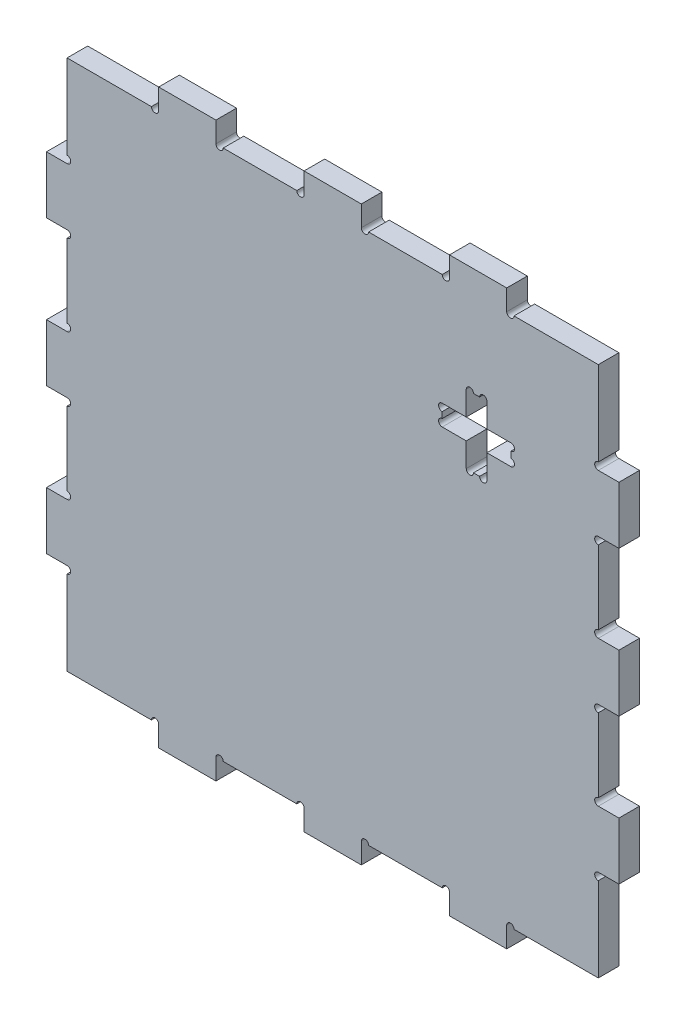
SolidWorks part; units mm, degrees
ref_plane "Piano frontale" through (0, 0, 0) normal (0, 0, 1) x (1, 0, 0)
ref_plane "Piano superiore" through (0, 0, 0) normal (0, 1, 0) x (1, 0, 0)
ref_plane "Piano destro" through (0, 0, 0) normal (1, 0, 0) x (0, 0, -1)
sketch "Schizzo1" plane through (0, 0, 0) normal (0, 0, 1) x (1, 0, 0)
  line L0 (-152, 250) -> (-152, 232)
  line L1 (-152, 250) -> (-102, 250)
  line L2 (232, 95.65) -> (232, 31.35)
  line L3 (232, 232) -> (232, 158.35)
  line L4 (250, 152) -> (250, 102)
  line L5 (-158.35, 232) -> (-232, 232)
  line L6 (-102, 250) -> (-102, 232)
  line L7 (-95.65, 232) -> (-31.35, 232)
  line L8 (-25, 232) -> (-25, 250)
  line L9 (-25, 250) -> (25, 250)
  line L10 (25, 250) -> (25, 232)
  line L11 (31.35, 232) -> (95.65, 232)
  line L12 (102, 232) -> (102, 250)
  line L13 (102, 250) -> (152, 250)
  line L14 (152, 250) -> (152, 232)
  line L15 (158.35, 232) -> (232, 232)
  line L16 (0, 0) -> (-543.7946, 0) construction
  line L17 (-25, 250) -> (25, 250)
  line L18 (102, 250) -> (152, 250)
  line L19 (0, 0) -> (250, 0) construction
  line L20 (127, -250) -> (127, -226.3396) construction
  line L21 (102, -250) -> (152, -250)
  line L22 (-25, -250) -> (25, -250)
  line L23 (152, -250) -> (152, -232)
  line L24 (102, -250) -> (152, -250)
  line L25 (102, -232) -> (102, -250)
  line L26 (31.35, -232) -> (95.65, -232)
  line L27 (25, -250) -> (25, -232)
  line L28 (-25, -250) -> (25, -250)
  line L29 (-25, -232) -> (-25, -250)
  line L30 (-95.65, -232) -> (-31.35, -232)
  line L31 (-102, -250) -> (-102, -232)
  line L32 (-152, -250) -> (-102, -250)
  line L33 (-152, -250) -> (-152, -232)
  line L34 (-158.35, 232) -> (-232, 232)
  line L35 (158.35, -232) -> (232, -232)
  line L36 (-232, -232) -> (-158.35, -232)
  line L37 (232, 152) -> (250, 152)
  line L38 (250, 152) -> (250, 102)
  line L39 (250, 102) -> (232, 102)
  line L40 (-232, -158.35) -> (-232, -232)
  line L41 (232, 25) -> (250, 25)
  line L42 (250, 25) -> (250, -25)
  line L43 (250, -25) -> (232, -25)
  line L44 (232, -31.35) -> (232, -95.65)
  line L45 (232, -102) -> (250, -102)
  line L46 (250, -102) -> (250, -152)
  line L47 (250, -152) -> (232, -152)
  line L48 (232, -158.35) -> (232, -232)
  line L49 (0, 0) -> (0, 361.2155) construction
  line L50 (-232, 232) -> (-232, 158.35)
  line L51 (-250, -152) -> (-232, -152)
  line L52 (-250, -102) -> (-250, -152)
  line L53 (250, 0) -> (195.0164, 0) construction
  line L54 (-232, -102) -> (-250, -102)
  line L55 (-232, -31.35) -> (-232, -95.65)
  line L56 (-250, -25) -> (-232, -25)
  line L57 (-250, 25) -> (-250, -25)
  line L58 (-232, 25) -> (-250, 25)
  line L59 (-250, 102) -> (-232, 102)
  line L60 (-250, 152) -> (-250, 102)
  line L61 (-232, 152) -> (-250, 152)
  line L62 (-250, 152) -> (-250, 102)
  line L63 (-232, 95.65) -> (-232, 31.35)
  line L64 (85.0518, 125.6467) -> (174.9168, 125.6467) construction
  line L65 (174.9168, 125.6467) -> (125.65, 90.1186) construction
  line L66 (125.65, 125.6467) -> (125.65, 176.559) construction
  line L67 (134.65, 95.6467) -> (133.3158, 95.6467)
  line L68 (134.65, 95.6467) -> (134.65, 116.6467)
  line L69 (95.65, 134.6467) -> (116.65, 134.6467)
  line L70 (95.65, 128.2967) -> (95.65, 122.9967)
  line L71 (95.65, 116.6467) -> (116.65, 116.6467)
  line L72 (155.65, 128.2967) -> (155.65, 122.9967)
  line L73 (128.3, 155.6467) -> (123, 155.6467)
  line L74 (116.65, 95.6467) -> (116.65, 116.6467)
  line L75 (128.3, 95.6467) -> (123, 95.6467)
  line L77 (134.65, 134.6467) -> (155.65, 134.6467)
  line L78 (134.65, 134.6467) -> (134.65, 155.6467)
  line L79 (134.65, 116.6467) -> (155.65, 116.6467)
  line L81 (116.65, 134.6467) -> (116.65, 155.6467)
  arc A0 (-152, 232) -> (-158.35, 232) centre (-155.175, 232) cw
  arc A1 (102, 232) -> (95.65, 232) centre (98.825, 232) cw
  arc A2 (-102, 232) -> (-95.65, 232) centre (-98.825, 232) ccw
  arc A3 (-25, 232) -> (-31.35, 232) centre (-28.175, 232) cw
  arc A4 (25, 232) -> (31.35, 232) centre (28.175, 232) ccw
  arc A5 (152, 232) -> (158.35, 232) centre (155.175, 232) ccw
  arc A6 (152, -232) -> (158.35, -232) centre (155.175, -232) cw
  arc A7 (25, -232) -> (31.35, -232) centre (28.175, -232) cw
  arc A8 (-25, -232) -> (-31.35, -232) centre (-28.175, -232) ccw
  arc A9 (-102, -232) -> (-95.65, -232) centre (-98.825, -232) cw
  arc A10 (102, -232) -> (95.65, -232) centre (98.825, -232) ccw
  arc A11 (-152, -232) -> (-158.35, -232) centre (-155.175, -232) ccw
  arc A12 (232, 102) -> (232, 95.65) centre (232, 98.825) ccw
  arc A13 (232, 152) -> (232, 158.35) centre (232, 155.175) cw
  arc A14 (232, -25) -> (232, -31.35) centre (232, -28.175) ccw
  arc A15 (232, 25) -> (232, 31.35) centre (232, 28.175) cw
  arc A16 (232, -102) -> (232, -95.65) centre (232, -98.825) cw
  arc A17 (232, -152) -> (232, -158.35) centre (232, -155.175) ccw
  arc A18 (-232, -152) -> (-232, -158.35) centre (-232, -155.175) cw
  arc A19 (-232, -102) -> (-232, -95.65) centre (-232, -98.825) ccw
  arc A20 (-232, 25) -> (-232, 31.35) centre (-232, 28.175) ccw
  arc A21 (-232, -25) -> (-232, -31.35) centre (-232, -28.175) cw
  arc A22 (-232, 152) -> (-232, 158.35) centre (-232, 155.175) ccw
  arc A23 (-232, 102) -> (-232, 95.65) centre (-232, 98.825) cw
  arc A24 (134.65, 155.6467) -> (128.3, 155.6467) centre (131.475, 155.6467) ccw
  arc A25 (116.65, 155.6467) -> (123, 155.6467) centre (119.825, 155.6467) cw
  arc A26 (134.65, 95.6467) -> (128.3, 95.6467) centre (131.475, 95.6467) cw
  arc A27 (116.65, 95.6467) -> (123, 95.6467) centre (119.825, 95.6467) ccw
  arc A28 (95.65, 116.6467) -> (95.65, 122.9967) centre (95.65, 119.8217) cw
  arc A29 (95.65, 134.6467) -> (95.65, 128.2967) centre (95.65, 131.4717) ccw
  arc A30 (155.65, 116.6467) -> (155.65, 122.9967) centre (155.65, 119.8217) ccw
  arc A31 (155.65, 134.6467) -> (155.65, 128.2967) centre (155.65, 131.4717) cw
  point P31 (250, 0)
  point P33 (-250, 0)
  point P113 (125.65, 125.6467)
  dimension "D9" = 18
  dimension "D12" = 3.175
  dimension "D3" = 60
  dimension "D20" = 3.175
  dimension "D22" = 3.175
  dimension "D4" = 250
  dimension "D5" = 18
  dimension "D6" = 18
  dimension "D7" = 77
  dimension "D8" = 77
  dimension "D10" = 50
  dimension "D11" = 50
  dimension "D13" = 60
  dimension "D14" = 98
  dimension "D15" = 50
  dimension "D16" = 77
  dimension "D17" = 50
  dimension "D18" = 77
  dimension "D19" = 50
  dimension "D21" = 18
extrude "Estrusione-Estrusione1" add sketch "Schizzo1" along normal blind 18 contours L59 A23 L63 A20 L58 L57 L56 A21 L55 A19 L54 L52 L51 A18 L40 L36 A11 L33 L32 L31 A9 L30 A8 L29 L22 L27 A7 L26 A10 L25 L21 L23 A6 L35 L48 A17 L47 L46 L45 A16 L44 A14 L43 L42 L41 A15 L2 A12 L39 L4 L37
